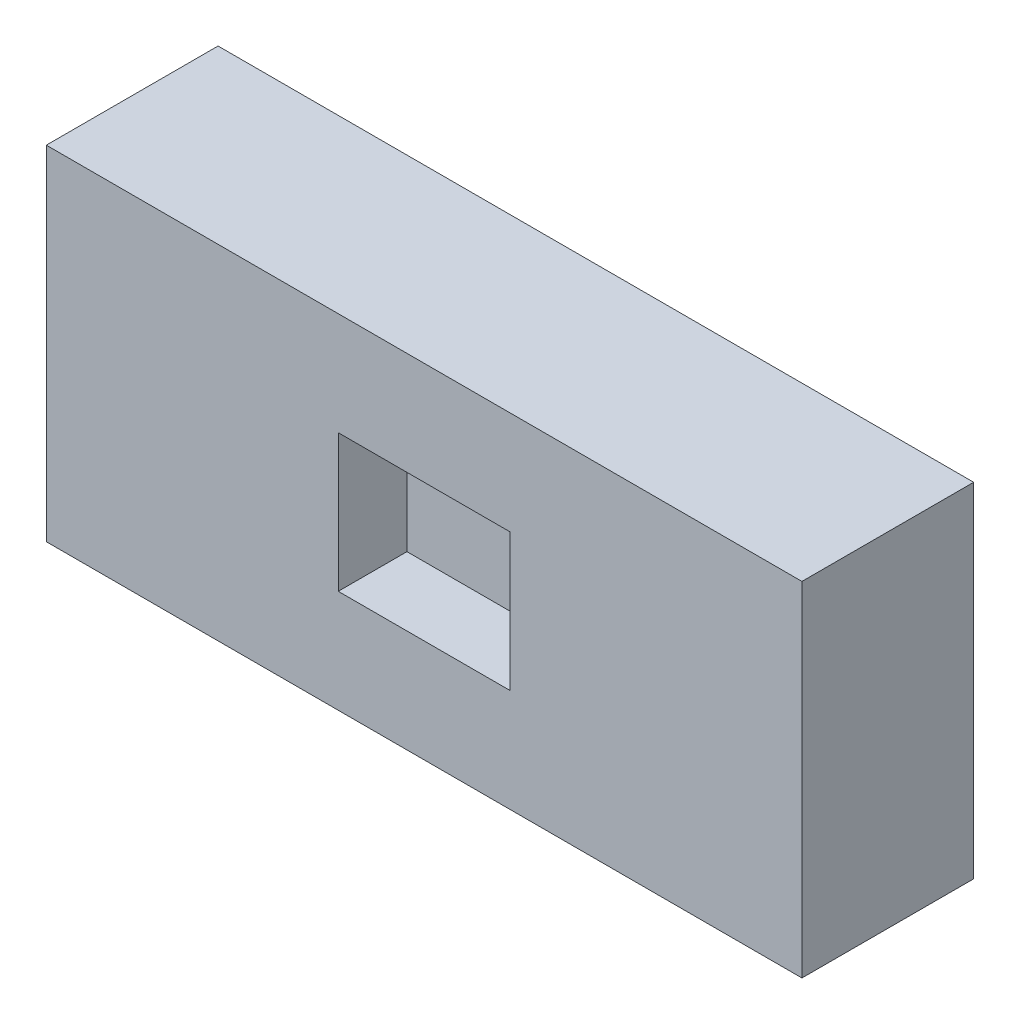
SolidWorks part; units mm, degrees
ref_plane "Front Plane" through (0, 0, 0) normal (0, 0, 1) x (1, 0, 0)
ref_plane "Top Plane" through (0, 0, 0) normal (0, 1, 0) x (1, 0, 0)
ref_plane "Right Plane" through (0, 0, 0) normal (1, 0, 0) x (0, 0, -1)
sketch "RectangleSketch" plane through (0, 0, 0) normal (0, 0, 1) x (1, 0, 0)
  line L1 (0, 0) -> (44, 0)
  line L2 (0, 0) -> (0, 20)
  line L3 (0, 20) -> (44, 20)
  line L4 (44, 0) -> (44, 20)
  dimension "width_mm" = 44
  dimension "height_mm" = 20
extrude "BlindBoss" add sketch "RectangleSketch" along normal blind 10 separate body
sketch "CutSketch" plane through (0, 0, 10) normal (0, 0, 1) x (1, 0, 0)
  line L1 (17, 6) -> (27, 6)
  line L2 (17, 6) -> (17, 14)
  line L3 (17, 14) -> (27, 14)
  line L4 (27, 6) -> (27, 14)
  dimension "cut_width_mm" = 10
  dimension "cut_height_mm" = 8
  dimension "cut_left_mm" = 17
  dimension "cut_bottom_mm" = 6
extrude "BlindCut" cut sketch "CutSketch" against normal blind 4
equation "\"cut_left_mm@CutSketch\" = (\"width_mm@RectangleSketch\" - \"cut_width_mm@CutSketch\") / 2"
equation "\"cut_bottom_mm@CutSketch\" = (\"height_mm@RectangleSketch\" - \"cut_height_mm@CutSketch\") / 2"
